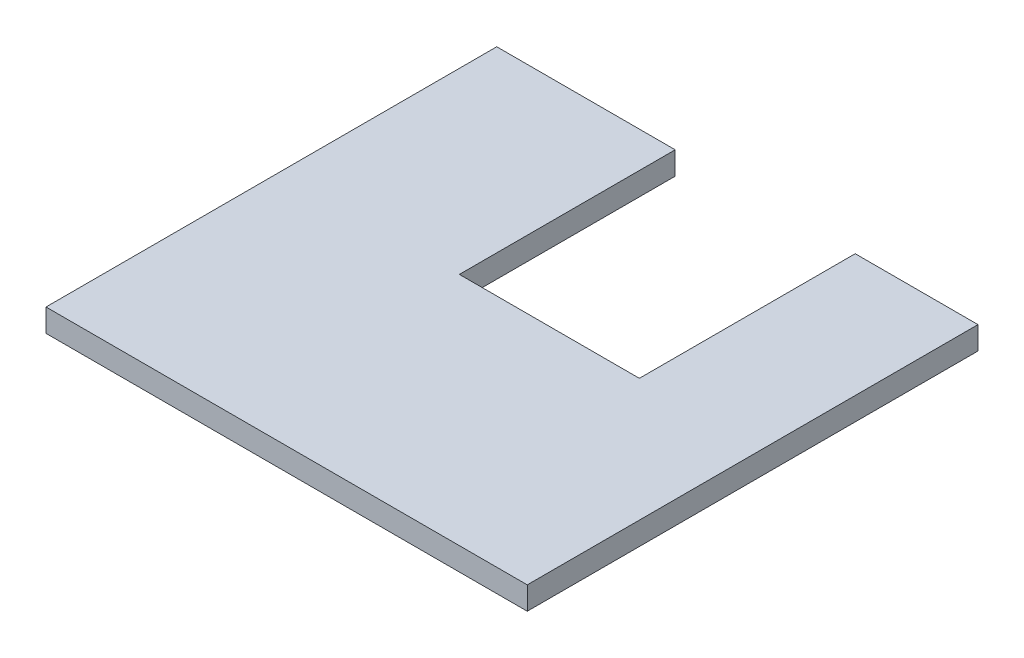
SolidWorks part; units mm, degrees
ref_plane "Front Plane" through (0, 0, 0) normal (0, 0, 1) x (1, 0, 0)
ref_plane "Top Plane" through (0, 0, 0) normal (0, 1, 0) x (1, 0, 0)
ref_plane "Right Plane" through (0, 0, 0) normal (1, 0, 0) x (0, 0, -1)
sketch "Sketch3" plane through (0, 0, 0) normal (0, 1, 0) x (1, 0, 0)
  line L1 (0, 0) -> (23.6, 0)
  line L2 (0, 0) -> (0, 28.3)
  line L3 (0, 28.3) -> (23.6, 28.3)
  line L4 (23.6, 0) -> (23.6, 28.3)
  line L5 (-23.4, 28.3) -> (39.7, 28.3)
  line L6 (-23.4, 28.3) -> (-23.4, -30.8)
  line L7 (-23.4, -30.8) -> (39.7, -30.8)
  line L8 (39.7, 28.3) -> (39.7, -30.8)
  dimension "D1" = 28.3
  dimension "D2" = 23.6
  dimension "D3" = 59.1
  dimension "D4" = 63.1
  dimension "D5" = 23.4
extrude "Boss-Extrude1" add sketch "Sketch3" along normal blind 3 contours L2 L1 L4 L3 | L6 L5 L8 L7
